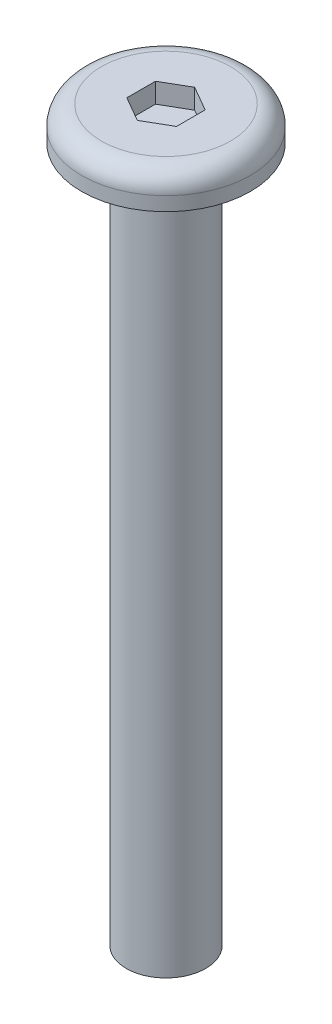
SolidWorks part; units mm, degrees
material "AISI 304"
ref_plane "前视基准面" through (0, 0, 0) normal (0, 0, 1) x (1, 0, 0)
ref_plane "上视基准面" through (0, 0, 0) normal (0, 1, 0) x (1, 0, 0)
ref_plane "右视基准面" through (0, 0, 0) normal (1, 0, 0) x (0, 0, -1)
other "Configuration Table"
sketch "草图1" plane through (0, 0, 0) normal (0, 1, 0) x (1, 0, 0)
  circle A0 centre (0, 0) radius 2
  circle A1 centre (0, 0) radius 1.5
  dimension "D1" = 4
  dimension "D2" = 3
extrude "凸台-拉伸1" add sketch "草图1" along normal blind 35
sketch "草图2" plane through (0, 35, 0) normal (0, 1, 0) x (1, 0, 0)
  circle A0 centre (0, 0) radius 4.25
  dimension "D1" = 8.5
extrude "凸台-拉伸2" add sketch "草图2" along normal blind 1.7
sketch "草图3" plane through (0, 36.7, 0) normal (0, 1, 0) x (1, 0, 0)
  line L0 (0, 0) -> (0, 6.6493) construction
  line L1 (1.25, 0.7217) -> (0, 1.4434)
  line L2 (0, 1.4434) -> (-1.25, 0.7217)
  line L3 (-1.25, 0.7217) -> (-1.25, -0.7217)
  line L4 (-1.25, -0.7217) -> (0, -1.4434)
  line L5 (0, -1.4434) -> (1.25, -0.7217)
  line L6 (1.25, -0.7217) -> (1.25, 0.7217)
  circle A0 centre (0, 0) radius 1.25 construction
  dimension "D1" = 2.5
extrude "切除-拉伸1" cut sketch "草图3" against normal blind 1
fillet "圆角1" radius 1 1 edges at (0, 36.7, 4.25)
